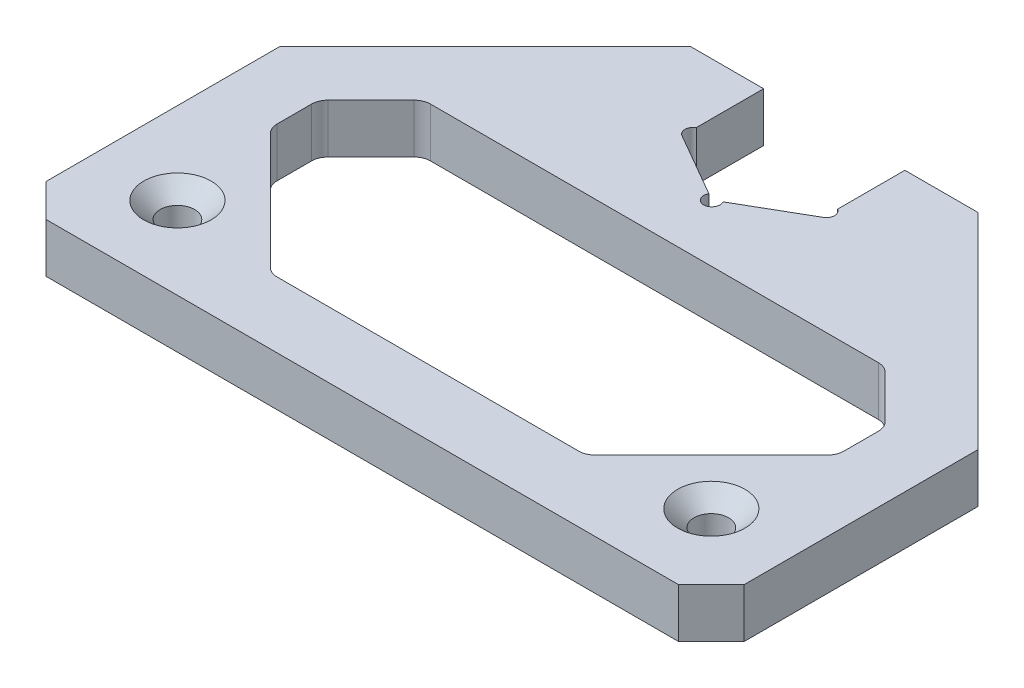
SolidWorks part; units mm, degrees
ref_plane "前视基准面" through (0, 0, 0) normal (0, 0, 1) x (1, 0, 0)
ref_plane "上视基准面" through (0, 0, 0) normal (0, 1, 0) x (1, 0, 0)
ref_plane "右视基准面" through (0, 0, 0) normal (1, 0, 0) x (0, 0, -1)
sketch "草图1" plane through (0, 0, 0) normal (0, 1, 0) x (1, 0, 0)
  line L0 (-32.5, -42.5) -> (32.5, -42.5) construction
  line L1 (0, 9.9304) -> (-8.6, 4.9652) construction
  line L2 (-8.6, 4.9652) -> (-8.6, -4.9652)
  line L3 (-8.6, -4.9652) -> (0, -9.9304)
  line L4 (0, -9.9304) -> (8.6, -4.9652)
  line L5 (8.6, -4.9652) -> (8.6, 4.9652)
  line L6 (8.6, 4.9652) -> (0, 9.9304) construction
  line L7 (-8.6, 4.9652) -> (-42.5, 4.9652)
  line L8 (-42.5, 4.9652) -> (-42.5, -52.5)
  line L9 (-42.5, -52.5) -> (42.5, -52.5)
  line L10 (42.5, -52.5) -> (42.5, 4.9652)
  line L11 (42.5, 4.9652) -> (8.6, 4.9652)
  circle A0 centre (0, 0) radius 8.6 construction
  circle A1 centre (-32.5, -42.5) radius 2.1
  circle A2 centre (32.5, -42.5) radius 2.1
  point P13 (0, -42.5)
  dimension "D1" = 17.2
  dimension "D2" = 65
  dimension "D3" = 4.2
  dimension "D4" = 42.5
  dimension "D5" = 10
  dimension "D6" = 10
  dimension "D7" = 10
extrude "凸台-拉伸1" add sketch "草图1" along normal mid plane 6
chamfer "倒角1" distance 25 angle 45 2 edges at (42.5, 0, -4.9652) (-42.5, 0, -4.9652)
sketch "草图4" plane through (0, 3, 0) normal (0, 1, 0) x (1, 0, 0)
  line L0 (0, -9.9304) -> (-8.6, -4.9652) construction
  line L1 (8.6, -4.9652) -> (0, -9.9304) construction
  circle A0 centre (0, -9.9304) radius 1
  circle A1 centre (-8.1, -4.0992) radius 1
  circle A2 centre (8.1, -4.0992) radius 1
  dimension "D1" = 2
extrude "切除-拉伸1" cut sketch "草图4" against normal through all
sketch "草图3" plane through (0, 3, 0) normal (0, 1, 0) x (1, 0, 0)
  line L0 (-28.0819, -16.9304) -> (-34.5, -23.3485)
  line L1 (-34.5, -23.3485) -> (-34.5, -29.1863)
  line L2 (-34.5, -29.1863) -> (-19.1863, -44.5)
  line L3 (-19.1863, -44.5) -> (19.1863, -44.5)
  line L4 (19.1863, -44.5) -> (34.5, -29.1863)
  line L5 (34.5, -23.3485) -> (28.0819, -16.9304)
  line L6 (28.0819, -16.9304) -> (-28.0819, -16.9304)
  line L7 (34.5, -23.3485) -> (34.5, -29.1863)
  line L8 (-17.5, 4.9652) -> (-42.5, -20.0348) construction
  line L10 (42.5, -20.0348) -> (17.5, 4.9652) construction
  line L11 (-42.5, -52.5) -> (42.5, -52.5) construction
  line L12 (-42.5, -20.0348) -> (-42.5, -52.5) construction
  circle A0 centre (-32.5, -42.5) radius 2.1 construction
  arc A1 (-0.866, -9.4304) -> (0.866, -9.4304) centre (0, -9.9304) ccw construction
  dimension "D6" = 8
  dimension "D1" = 8
  dimension "D2" = 8
  dimension "D3" = 8
  dimension "D4" = 45
  dimension "D5" = 8
  dimension "D7" = 7
extrude "切除-拉伸2" cut sketch "草图3" against normal through all
chamfer "倒角2" distance 4 angle 45 2 edges at (42.5, 0, 52.5) (-42.5, 0, 52.5)
fillet "圆角1" radius 2 8 edges at (34.5, 0, 23.3485) (34.5, 0, 29.1863) (19.1863, 0, 44.5) (-19.1863, 0, 44.5) (-34.5, 0, 29.1863) (-34.5, 0, 23.3485) (28.0819, 0, 16.9304) (-28.0819, 0, 16.9304)
chamfer "倒角3" distance 2 angle 45 2 edges at (32.5, 3, 44.6) (-32.5, 3, 44.6)
